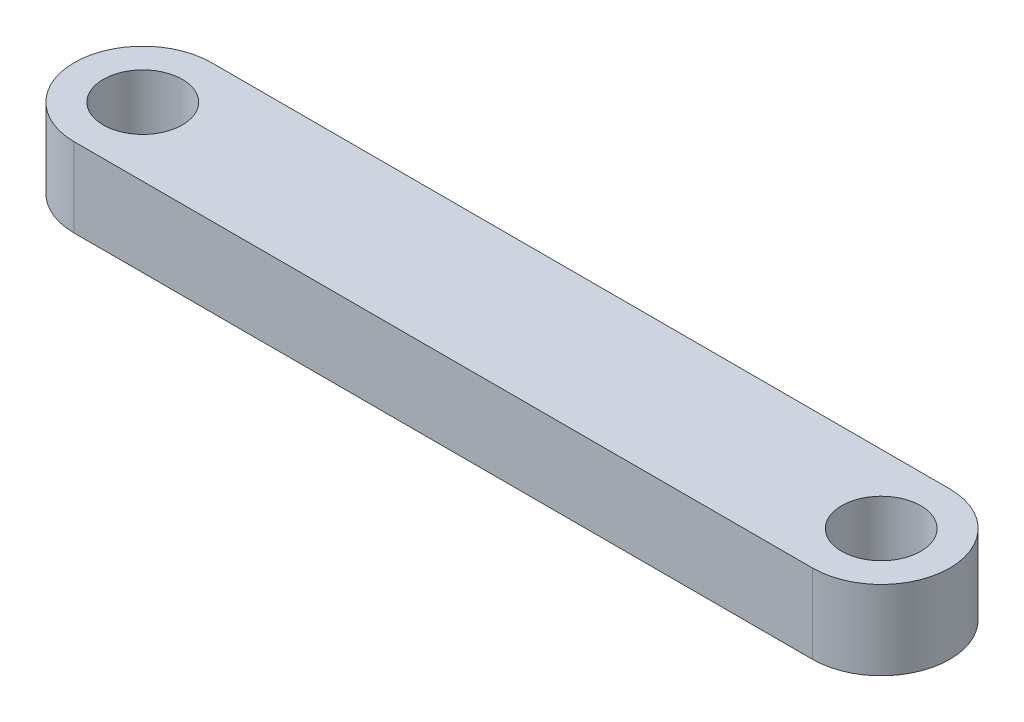
SolidWorks part; units mm, degrees
ref_plane "Front Plane" through (0, 0, 0) normal (0, 0, 1) x (1, 0, 0)
ref_plane "Top Plane" through (0, 0, 0) normal (0, 1, 0) x (1, 0, 0)
ref_plane "Right Plane" through (0, 0, 0) normal (1, 0, 0) x (0, 0, -1)
sketch "Sketch1" plane through (0, 0, 0) normal (0, -1, 0) x (1, 0, 0)
  line L0 (-70, 0) -> (70, 0) construction
  line L1 (-70, 13) -> (70, 13)
  line L2 (-70, -13) -> (70, -13)
  circle A0 centre (-70, 0) radius 7.5
  circle A1 centre (-70, 0) radius 7.5
  arc A2 (-70, 13) -> (-70, -13) centre (-70, 0) ccw
  arc A3 (70, -13) -> (70, 13) centre (70, 0) ccw
  circle A4 centre (70, 0) radius 7.5
  point P3 (0, 0)
  dimension "D3" = 15
  dimension "D1" = 140
  dimension "D2" = 13
extrude "Boss-Extrude1" add sketch "Sketch1" against normal blind 15
